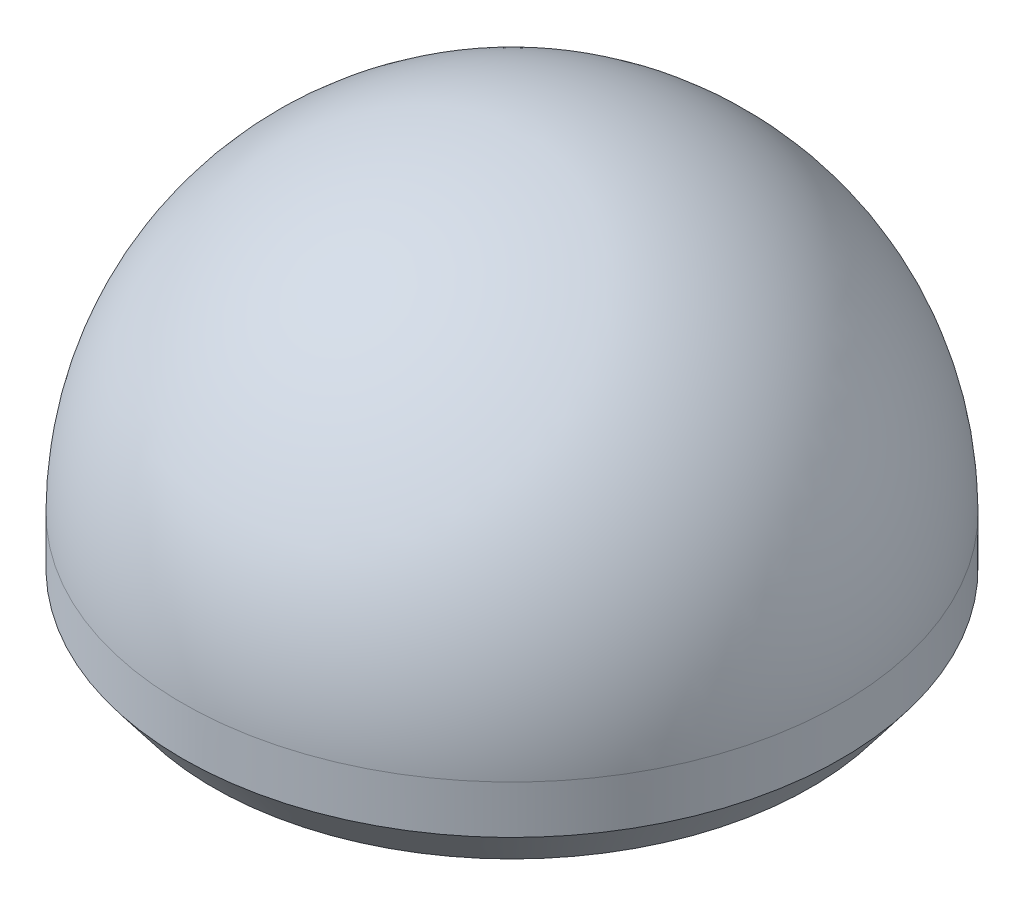
SolidWorks part; units mm, degrees
ref_plane "Front Plane" through (0, 0, 0) normal (0, 0, 1) x (1, 0, 0)
ref_plane "Top Plane" through (0, 0, 0) normal (0, 1, 0) x (1, 0, 0)
ref_plane "Right Plane" through (0, 0, 0) normal (1, 0, 0) x (0, 0, -1)
sketch "Sketch1" plane through (0, 0, 0) normal (0, 0, 1) x (1, 0, 0)
  line L0 (-150, 0) -> (-150, -21.8397)
  line L1 (-150, -21.8397) -> (-135.9926, -40.2239)
  line L3 (0, 0) -> (0, 150)
  arc A0 (0, 150) -> (-150, 0) centre (0, 0) ccw
  arc A2 (0, 0) -> (-135.9926, -40.2239) centre (0, -250) ccw
  dimension "D1" = 300
  dimension "D2" = 500
revolve "Revolve1" add sketch "Sketch1" angle 360 about L3
sketch "Sketch2" plane through (0, 0, 0) normal (0, 0, 1) x (1, 0, 0)
  line L1 (88.9252, -25.6799) -> (88.9252, 14.3201)
  arc A0 (135.9926, -40.2239) -> (-135.9926, -40.2239) centre (0, -250) ccw
  arc A1 (88.9252, -25.6799) -> (88.9252, 14.3201) centre (88.9252, -5.6799) ccw
  dimension "D2" = 500
  dimension "D3" = 20
  dimension "D1" = 40
  dimension "D4" = 260
sketch "Sketch3" plane through (0, 0, 0) normal (0, 0, 1) x (1, 0, 0)
  line L0 (0, -45.0192) -> (0, 68.2874)
revolve "Cut-Revolve2" cut sketch "Sketch2" angle 360 about L1
pattern_circular "CirPattern2" count 4 every 90 about axis through (0, 0, 0) along (0, 1, 0) of "Cut-Revolve2"
